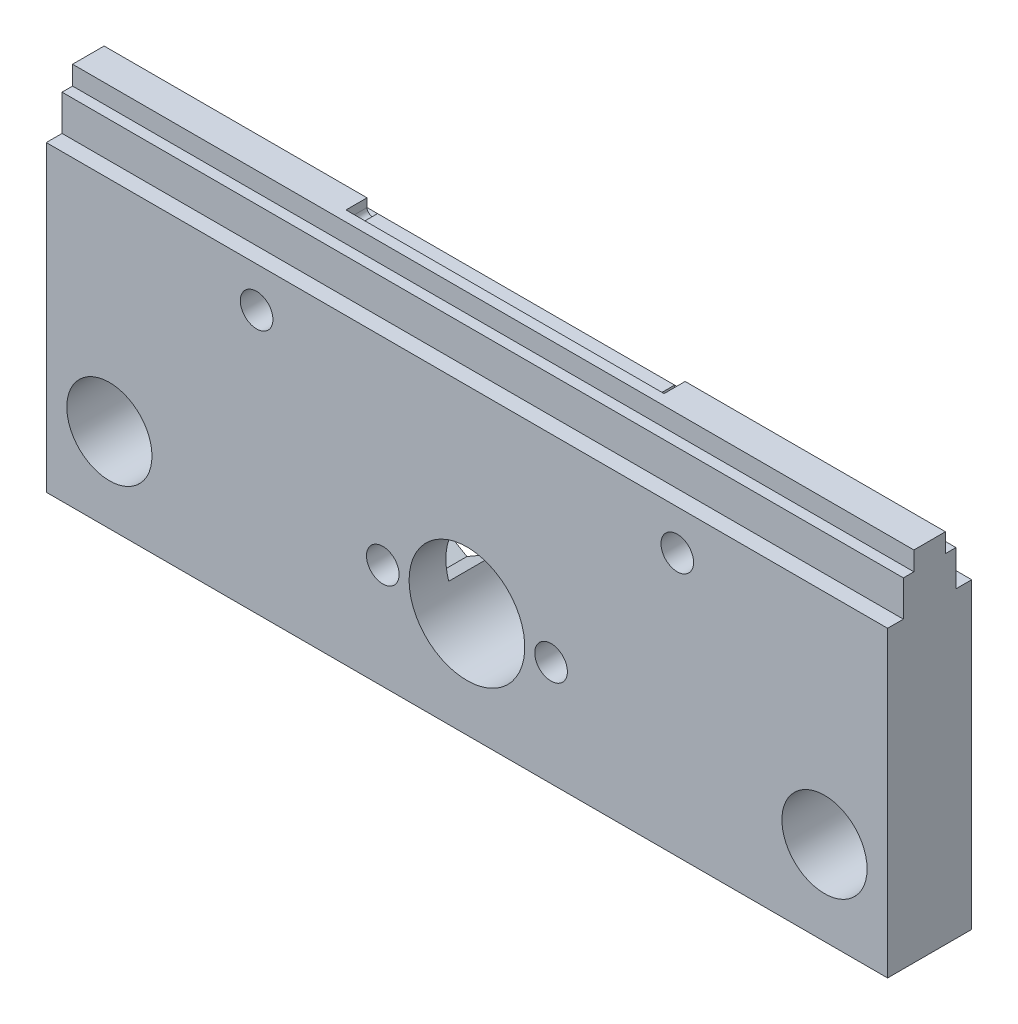
SolidWorks part; units mm, degrees
ref_plane "前视基准面" through (0, 0, 0) normal (0, 0, 1) x (1, 0, 0)
ref_plane "上视基准面" through (0, 0, 0) normal (0, 1, 0) x (1, 0, 0)
ref_plane "右视基准面" through (0, 0, 0) normal (1, 0, 0) x (0, 0, -1)
sketch "前视图草图" plane through (0, 0, 0) normal (0, 0, 1) x (1, 0, 0)
  line L0 (0, 0) -> (44.4821, 0) construction
  line L1 (0, 0) -> (0, 28.3185) construction
sketch "草图2" plane through (0, 0, 0) normal (0, 0, 1) x (1, 0, 0)
  line L0 (0, 0) -> (80, 0)
  line L1 (-200000, 0) -> (200044.4821, 0) construction
  line L2 (80, 0) -> (80, 34)
  line L3 (80, 34) -> (0, 34)
  line L4 (0, -200000) -> (0, 200028.3185) construction
  line L5 (0, 34) -> (0, 0)
  circle A0 centre (6, 8) radius 4.05
  circle A1 centre (40, 10) radius 4.05
  circle A2 centre (74, 8) radius 4.05
  dimension "D3" = 8
  dimension "D5" = 10
  dimension "D9" = 8.1
  dimension "D10" = 8.1
  dimension "D11" = 8.1
  dimension "D1" = 34
  dimension "D2" = 80
  dimension "D4" = 6
  dimension "D6" = 6
  dimension "D7" = 8
  dimension "D8" = 40
extrude "凸台-拉伸1" add sketch "草图2" along normal blind 8
sketch "草图3" plane through (0, 0, 8) normal (0, 0, 1) x (1, 0, 0)
  line L0 (16.088, 8) -> (31.4805, 8) construction
  line L1 (6, 8) -> (6, 16.8386) construction
  line L2 (74, 8) -> (74, 16.5917) construction
  line L4 (-200000, 0) -> (200044.4821, 0) construction
  circle A2 centre (22, 8) radius 2.55
  circle A3 centre (58, 8) radius 2.55
  dimension "D4" = 5.1
  dimension "D5" = 5.1
  dimension "D1" = 8
  dimension "D2" = 16
  dimension "D3" = 16
extrude "切除-拉伸1" [suppressed] cut sketch "草图3" against normal through all
sketch "草图4" plane through (80, 0, 0) normal (1, 0, 0) x (0, 0, -1)
  line L1 (0, -200000) -> (0, 200028.3185) construction
  line L2 (-1.5, 32.2) -> (-2.5, 32.2)
  line L3 (-2.5, 32.2) -> (-2.5, 34)
  line L4 (-8, 34) -> (0, 34) construction
  line L5 (-2.5, 34) -> (0, 34)
  line L6 (-1.5, 32.2) -> (-1.5, 28.8)
  line L7 (-1.5, 28.8) -> (0, 28.8)
  line L8 (0, 28.8) -> (0, 34)
  line L9 (-4, 0) -> (-4, 34) construction
  line L10 (-8, 0) -> (0, 0) construction
  line L11 (-6.5, 32.2) -> (-6.5, 28.8)
  line L12 (-6.5, 28.8) -> (-8, 28.8)
  line L13 (-8, 28.8) -> (-8, 34)
  line L14 (-5.5, 34) -> (-8, 34)
  line L15 (-5.5, 32.2) -> (-5.5, 34)
  line L16 (-6.5, 32.2) -> (-5.5, 32.2)
  dimension "D1" = 3.4
  dimension "D2" = 2.5
  dimension "D3" = 1.5
  dimension "D4" = 1.8
extrude "切除-拉伸2" cut sketch "草图4" against normal through all
sketch "草图5" plane through (0, 0, 8) normal (0, 0, 1) x (1, 0, 0)
  line L0 (40, 10) -> (56.5376, 10) construction
  circle A0 centre (40, 10) radius 8 construction
  circle A1 centre (48, 10) radius 1.55
  circle A2 centre (32, 10) radius 1.55
  dimension "D1" = 3.1
  dimension "D2" = 3.1
  dimension "D3" = 16
extrude "切除-拉伸3" cut sketch "草图5" against normal through all
sketch "草图7" [suppressed] plane through (0, 0, 0) normal (0, 0, -1) x (-1, 0, 0)
  line L0 (-80, 0) -> (-80, 28.8) construction
  line L1 (-53.9, 5.6329) -> (-53.9, 10.3671)
  line L14 (-53.9, 10.3671) -> (-58, 12.7343)
  line L15 (-58, 12.7343) -> (-62.1, 10.3671)
  line L19 (-62.1, 10.3671) -> (-62.1, 5.6329)
  line L20 (-62.1, 5.6329) -> (-58, 3.2657)
  line L21 (-58, 3.2657) -> (-53.9, 5.6329)
  line L22 (-17.9, 5.6329) -> (-17.9, 10.3671)
  line L23 (-17.9, 10.3671) -> (-22, 12.7343)
  line L24 (-22, 12.7343) -> (-26.1, 10.3671)
  line L25 (-26.1, 10.3671) -> (-26.1, 5.6329)
  line L26 (-26.1, 5.6329) -> (-22, 3.2657)
  line L27 (-22, 3.2657) -> (-17.9, 5.6329)
  circle A6 centre (-58, 8) radius 4.1 construction
  circle A10 centre (-22, 8) radius 4.1 construction
  dimension "D1" = 8.2
sketch "草图8" plane through (0, 0, 0) normal (0, 0, -1) x (-1, 0, 0)
  line L0 (-80, 0) -> (-80, 28.8) construction
  line L1 (-45.15, 8.3546) -> (-45.15, 11.6454)
  line L5 (-45.15, 11.6454) -> (-48, 13.2909)
  line L6 (-48, 13.2909) -> (-50.85, 11.6454)
  line L7 (-50.85, 11.6454) -> (-50.85, 8.3546)
  line L8 (-50.85, 8.3546) -> (-48, 6.7091)
  line L9 (-48, 6.7091) -> (-45.15, 8.3546)
  line L10 (-29.15, 8.3546) -> (-29.15, 11.6454)
  line L11 (-29.15, 11.6454) -> (-32, 13.2909)
  line L12 (-32, 13.2909) -> (-34.85, 11.6454)
  line L13 (-34.85, 11.6454) -> (-34.85, 8.3546)
  line L14 (-34.85, 8.3546) -> (-32, 6.7091)
  line L15 (-32, 6.7091) -> (-29.15, 8.3546)
  circle A2 centre (-48, 10) radius 2.85 construction
  circle A3 centre (-32, 10) radius 2.85 construction
  dimension "D1" = 5.7
extrude "切除-拉伸5" cut sketch "草图8" against normal blind 4.5
sketch "草图11" plane through (0, 0, 0) normal (0, 0, -1) x (-1, 0, 0)
  line L0 (0, 34) -> (-80, 34) construction
  line L1 (-80, 0) -> (-80, 28.8) construction
  line L2 (0, -200000) -> (0, 200028.3185) construction
  line L3 (-40, 20) -> (-40, 13.5744) construction
  line L4 (-28.772, 25) -> (-45.9396, 25) construction
  circle A0 centre (-60, 25) radius 1.55
  circle A1 centre (-20, 25) radius 1.55
  point P23 (-40, 20)
  dimension "D1" = 3.1
  dimension "D2" = 3.1
  dimension "D3" = 20
  dimension "D4" = 20
  dimension "D5" = 9
sketch "草图20" plane through (0, 0, 0) normal (0, 0, -1) x (-1, 0, 0)
  circle A0 centre (-40, 10) radius 5.5
  dimension "D1" = 11
extrude "切除-拉伸7" cut sketch "草图11" against normal through all contours A0 | A1
sketch "草图12" plane through (0, 0, 0) normal (0, 0, -1) x (-1, 0, 0)
  line L0 (-62.5, 22.15) -> (-57.5, 22.15)
  line L1 (-57.5, 27.85) -> (-62.5, 27.85)
  line L4 (-80, 0) -> (-80, 28.8) construction
  line L5 (-39.1423, 25) -> (-43.2672, 25) construction
  line L6 (-60, 21) -> (-60, 25.2385) construction
  line L7 (-20, 21) -> (-20, 26.1603) construction
  line L8 (-40, 20) -> (-40, 24.3689) construction
  line L9 (-17.5, 27.85) -> (-22.5, 27.85)
  line L10 (-22.5, 22.15) -> (-17.5, 22.15)
  line L11 (0, -200000) -> (0, 200028.3185) construction
  line L12 (0, 34) -> (-80, 34) construction
  arc A0 (-62.5, 27.85) -> (-62.5, 22.15) centre (-62.5, 25) ccw
  arc A1 (-57.5, 22.15) -> (-57.5, 27.85) centre (-57.5, 25) ccw
  arc A4 (-17.5, 22.15) -> (-17.5, 27.85) centre (-17.5, 25) ccw
  arc A5 (-22.5, 27.85) -> (-22.5, 22.15) centre (-22.5, 25) ccw
  point P16 (-38, 21)
  point P28 (-40, 25)
  dimension "D2" = 20
  dimension "D3" = 5
  dimension "D4" = 2.5
  dimension "D5" = 20
  dimension "D6" = 9
  dimension "D1" = 2
sketch "草图19" plane through (0, 0, 2.5) normal (0, 0, -1) x (-1, 0, 0)
  line L0 (0, 34) -> (-80, 34) construction
  line L1 (-25, 34) -> (-55.2479, 34)
  line L2 (-25, 34) -> (-25, 33.2)
  line L3 (-26, 33.2) -> (-54.2479, 33.2)
  line L4 (-55.2479, 34) -> (-55.2479, 33.2)
  line L5 (0, -200000) -> (0, 200028.3185) construction
  line L7 (0, 32.2) -> (-80, 32.2) construction
  line L8 (-56.3335, 32.7) -> (-52.9089, 32.7) construction
  line L9 (-55.2479, 1028.5823) -> (-55.2479, 33.2) construction
  line L10 (-25, 1028.5823) -> (-25, 32.7) construction
  line L11 (-55.2479, 32.7) -> (-55.2479, -973.3) construction
  line L12 (-25, 32.7) -> (-25, -973.3) construction
  arc A3 (-55.2479, 33.2) -> (-54.2479, 33.2) centre (-54.7479, 33.2) ccw
  arc A6 (-26, 33.2) -> (-25, 33.2) centre (-25.5, 33.2) ccw
  dimension "D3" = 1
  dimension "D4" = 1
  dimension "D2" = 0.8
  dimension "D1" = 0.5
  dimension "D9" = 25
extrude "切除-拉伸11" cut sketch "草图19" against normal blind 2
extrude "切除-拉伸13" [suppressed] cut sketch "草图7" against normal blind 6
extrude "切除-拉伸14" cut sketch "草图20" against normal through all
